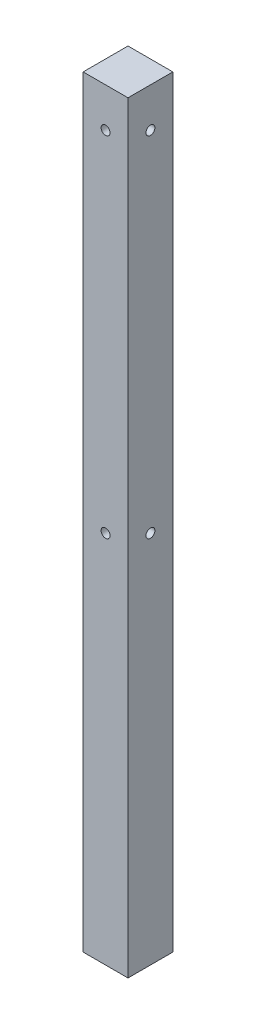
SolidWorks part; units mm, degrees
material "Concreto"
ref_plane "Plano frontal" through (0, 0, 0) normal (0, 0, 1) x (1, 0, 0)
ref_plane "Plano superior" through (0, 0, 0) normal (0, 1, 0) x (1, 0, 0)
ref_plane "Plano direito" through (0, 0, 0) normal (1, 0, 0) x (0, 0, -1)
sketch "Esboço1" plane through (0, 0, 0) normal (0, 1, 0) x (1, 0, 0)
  line L1 (-50, 50) -> (50, 50)
  line L2 (-50, 50) -> (-50, -50)
  line L3 (-50, -50) -> (50, -50)
  line L4 (50, 50) -> (50, -50)
  line L5 (-50, 50) -> (50, -50) construction
  line L6 (-50, -50) -> (50, 50) construction
  point P0 (0, 0)
  dimension "D1" = 100
  dimension "D2" = 100
extrude "Ressalto-extrusão1" add sketch "Esboço1" along normal blind 1700
hole_wizard "Furos-guia com Ø20.0mm1" positions "Esboço5" profile "Esboço4" hole size "Ø20.0" standard "Ansi Metric" end condition through all
sketch "Esboço5" plane through (50, 0, 0) normal (1, 0, 0) x (0, 0, -1)
  line L0 (-50, 0) -> (50, 0) construction
  line L1 (-50, 1700) -> (50, 1700) construction
  point P0 (0, 834.25)
  point P5 (0, 1612.2755)
  dimension "D1" = 834.25
sketch "Esboço4" plane through (50, 834.25, 0) normal (0, 1, 0) x (0, 0, -1)
  line L0 (0, 0) -> (0, 100)
  line L1 (0, 100) -> (10, 100)
  line L2 (10, 100) -> (10, 0)
  line L5 (10, 0) -> (0, 0)
  line L11 (0, -6.35) -> (0, 107.95) construction
  dimension "Thru Hole Dia." = 20
  dimension "Thru Hole Depth" = 100
hole_wizard "Furos-guia com Ø20.0mm2" positions "Esboço7" profile "Esboço8" hole size "Ø20.0" standard "Ansi Metric" end condition through all
sketch "Esboço7" plane through (0, 0, 50) normal (0, 0, 1) x (1, 0, 0)
  line L0 (-50, 1700) -> (50, 1700) construction
  point P0 (0, 834.25)
  point P4 (0, 1612.28)
  dimension "D1" = 834.25
  dimension "D2" = 87.72
sketch "Esboço8" plane through (0, 834.25, 50) normal (1, 0, 0) x (0, -1, 0)
  line L0 (0, 0) -> (0, 100)
  line L1 (0, 100) -> (10, 100)
  line L2 (10, 100) -> (10, 0)
  line L5 (10, 0) -> (0, 0)
  line L11 (0, -6.35) -> (0, 107.95) construction
  dimension "Thru Hole Dia." = 20
  dimension "Thru Hole Depth" = 100
